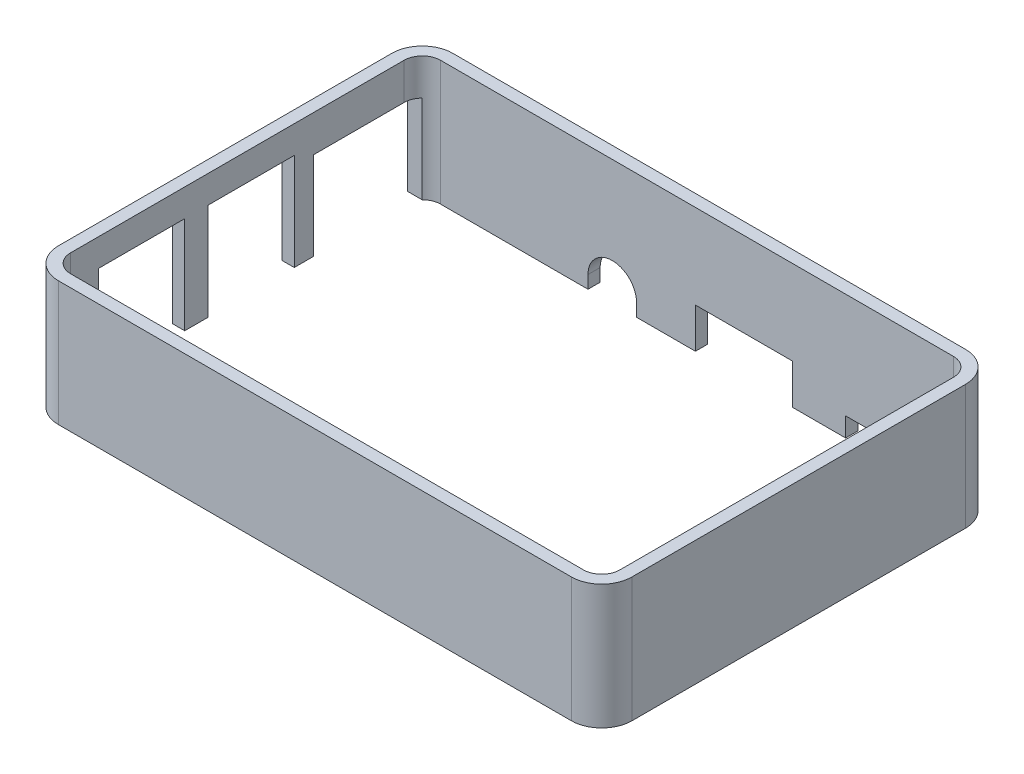
SolidWorks part; units mm, degrees
ref_plane "Front Plane" through (0, 0, 0) normal (0, 0, 1) x (1, 0, 0)
ref_plane "Top Plane" through (0, 0, 0) normal (0, 1, 0) x (1, 0, 0)
ref_plane "Right Plane" through (0, 0, 0) normal (1, 0, 0) x (0, 0, -1)
sketch "Sketch1" plane through (0, 0, 0) normal (0, 1, 0) x (1, 0, 0)
  line L0 (-97.6544, 2.6258) -> (-97.6544, -52.32)
  line L1 (-92.6544, 5.6258) -> (-8.1544, 5.6258)
  line L2 (-95.6544, 2.6258) -> (-95.6544, -52.32)
  line L3 (-92.6544, -55.32) -> (-8.1544, -55.32)
  line L4 (-5.1544, 2.6258) -> (-5.1544, -52.32)
  line L5 (-92.6544, -57.32) -> (-8.1544, -57.32)
  line L6 (-3.1544, 2.6258) -> (-3.1544, -52.32)
  line L7 (-92.6544, 7.6258) -> (-8.1544, 7.6258)
  line L8 (-3.1544, 7.6258) -> (-3.1544, -57.32) construction
  line L9 (-97.6544, 7.6258) -> (-3.1544, 7.6258) construction
  line L10 (-95.6544, 5.6258) -> (-5.1544, 5.6258) construction
  line L11 (-5.1544, 5.6258) -> (-5.1544, -55.32) construction
  line L12 (-97.6544, -57.32) -> (-3.1544, -57.32) construction
  line L13 (-95.6544, -55.32) -> (-5.1544, -55.32) construction
  line L14 (-95.6544, 5.6258) -> (-95.6544, -55.32) construction
  line L15 (-97.6544, 7.6258) -> (-97.6544, -57.32) construction
  line L16 (-8.1544, -16.2242) -> (-8.1544, -27.2242) construction
  line L17 (-25.4044, 7.6258) -> (-17.4044, 7.6258) construction
  line L18 (-86.6544, -52.32) -> (-10.6544, -52.32) construction
  line L19 (-97.6544, 4.2258) -> (-97.6544, -11.7742) construction
  arc A0 (-3.1544, 2.6258) -> (-8.1544, 7.6258) centre (-8.1544, 2.6258) ccw
  arc A1 (-8.1544, 5.6258) -> (-5.1544, 2.6258) centre (-8.1544, 2.6258) cw
  arc A2 (-8.1544, -57.32) -> (-3.1544, -52.32) centre (-8.1544, -52.32) ccw
  arc A3 (-8.1544, -55.32) -> (-5.1544, -52.32) centre (-8.1544, -52.32) ccw
  arc A4 (-95.6544, -52.32) -> (-92.6544, -55.32) centre (-92.6544, -52.32) ccw
  arc A5 (-97.6544, -52.32) -> (-92.6544, -57.32) centre (-92.6544, -52.32) ccw
  arc A6 (-97.6544, 2.6258) -> (-92.6544, 7.6258) centre (-92.6544, 2.6258) cw
  arc A7 (-92.6544, 5.6258) -> (-95.6544, 2.6258) centre (-92.6544, 2.6258) ccw
  point P32 (-101.312, -50.2971)
  point P33 (-9.7794, 7.811)
  point P38 (-8.1544, -53.5796)
  point P43 (-94.6544, 7.6258)
  dimension "D2" = 3
  dimension "D3" = 3
  dimension "D4" = 3
  dimension "D1" = 2
extrude "Boss-Extrude1" add sketch "Sketch1" along normal up to surface (20.53 mm away)
sketch "Sketch2" plane through (-97.6544, 0, 3.1544) normal (-1, 0, 0) x (0, 0, 1)
  line L1 (-7.8802, 0) -> (9.1198, 0)
  line L2 (-7.8802, 0) -> (-7.8802, 14.5)
  line L3 (-7.8802, 14.5) -> (9.1198, 14.5)
  line L4 (9.1198, 0) -> (9.1198, 14.5)
  line L6 (12.3198, 0) -> (26.5198, 0)
  line L7 (12.3198, 0) -> (12.3198, 16)
  line L8 (12.3198, 16) -> (26.5198, 16)
  line L9 (26.5198, 0) -> (26.5198, 16)
  line L10 (30.3698, 0) -> (44.5698, 0)
  line L11 (30.3698, 0) -> (30.3698, 16)
  line L12 (30.3698, 16) -> (44.5698, 16)
  line L13 (44.5698, 0) -> (44.5698, 16)
  line L22 (49.1656, 0) -> (-5.7802, 0) construction
  line L23 (-7.3802, 14) -> (-7.3802, 0) construction
  line L24 (-7.3802, 14) -> (8.6198, 14) construction
  line L25 (8.6198, 14) -> (8.6198, 0) construction
  line L26 (12.8198, 15.5) -> (12.8198, 0) construction
  line L27 (12.8198, 15.5) -> (26.0198, 15.5) construction
  line L28 (26.0198, 15.5) -> (26.0198, 0) construction
  line L29 (30.8698, 15.5) -> (30.8698, 0) construction
  point P4 (-33.6096, -35.5438)
  point P5 (44.6143, 13.9175)
  point P14 (30.191, 0)
  point P17 (26.3179, 15.4259)
  point P18 (10.273, 0)
  point P19 (6.3273, 15.4259)
  point P20 (-6.4689, 0)
  point P21 (-7.5208, 14.2998)
  point P22 (9.1457, 14.2332)
  point P29 (12.4079, 15.8079)
  point P30 (26.6185, 15.8833)
  point P31 (30.6534, 15.8833)
  dimension "D1" = 0.5
  dimension "D2" = 0.5
  dimension "D3" = 0.5
  dimension "D4" = 0.5
  dimension "D5" = 0.5
  dimension "D6" = 0.5
  dimension "D7" = 0.5
extrude "Cut-Extrude1" cut sketch "Sketch2" against normal up to next
sketch "Sketch3" plane through (0, 0, -7.6258) normal (0, 0, 1) x (1, 0, 0)
  line L0 (-92.6544, 0) -> (-8.1544, 0) construction
  line L1 (-25.9044, 0) -> (-16.9044, 0)
  line L2 (-25.9044, 0) -> (-25.9044, 3.16)
  line L3 (-25.9044, 3.16) -> (-16.9044, 3.16)
  line L4 (-16.9044, 0) -> (-16.9044, 3.16)
  line L5 (-60.8544, 5.6) -> (-60.8544, 0) construction
  line L6 (-34.6544, 0) -> (-50.6544, 0)
  line L7 (-34.6544, 0) -> (-34.6544, 6.6)
  line L8 (-34.6544, 6.6) -> (-50.6544, 6.6)
  line L9 (-50.6544, 0) -> (-50.6544, 6.6)
  line L10 (-68.3544, 0) -> (-60.3544, 0)
  line L11 (-68.3544, 0) -> (-68.3544, 2.1)
  line L13 (-60.3544, 0) -> (-60.3544, 2.1)
  line L14 (-67.8544, 5.6) -> (-67.8544, 0) construction
  line L15 (-62.7157, 6.1) -> (-65.5628, 6.1) construction
  line L16 (-60.8544, 5.6) -> (-67.8544, 5.6) construction
  line L17 (-35.1544, 6.1) -> (-35.1544, 0) construction
  line L18 (-35.1544, 6.1) -> (-50.1544, 6.1) construction
  line L19 (-50.1544, 6.1) -> (-50.1544, 0) construction
  line L20 (-17.4044, 2.66) -> (-17.4044, 0) construction
  line L21 (-25.4044, 2.66) -> (-17.4044, 2.66) construction
  line L22 (-25.4044, 2.66) -> (-25.4044, 0) construction
  arc A0 (-68.3544, 2.1) -> (-60.3544, 2.1) centre (-64.3544, 2.1) cw
  dimension "D4" = 0.5
  dimension "D1" = 0.5
  dimension "D2" = 0.5
  dimension "D3" = 0.5
  dimension "D5" = 0.5
  dimension "D6" = 0.5
  dimension "D7" = 0.5
  dimension "D8" = 0.5
  dimension "D9" = 0.5
extrude "Cut-Extrude2" cut sketch "Sketch3" along normal up to next
